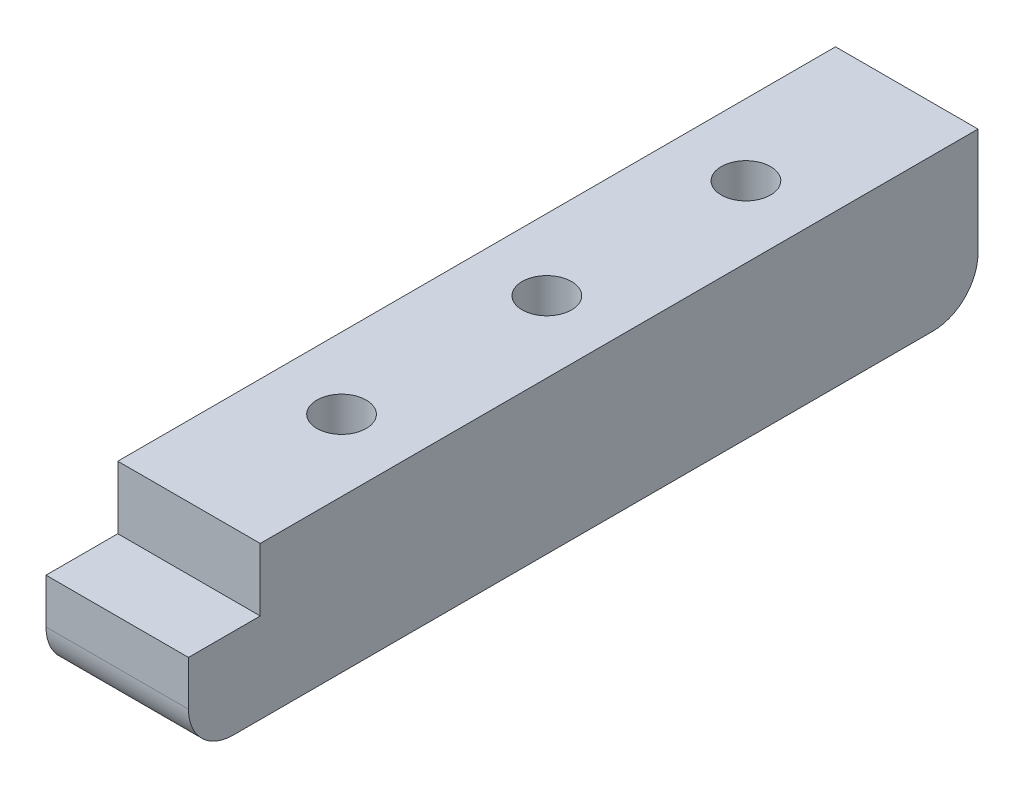
SolidWorks part; units mm, degrees
material "6063-T6"
ref_plane "Plano frontal" through (0, 0, 0) normal (0, 0, 1) x (1, 0, 0)
ref_plane "Plano superior" through (0, 0, 0) normal (0, 1, 0) x (1, 0, 0)
ref_plane "Plano direito" through (0, 0, 0) normal (1, 0, 0) x (0, 0, -1)
sketch "Esboço1" plane through (0, 0, 0) normal (1, 0, 0) x (0, 0, -1)
  line L1 (-17, -8.5) -> (63, -8.5)
  line L2 (-17, 1.5) -> (-17, 8.5)
  line L3 (-17, 8.5) -> (63, 8.5)
  line L4 (63, -8.5) -> (63, 8.5)
  line L7 (-17, -8.5) -> (-25, -8.5)
  line L9 (-17, 1.5) -> (-25, 1.5)
  line L10 (-25, -8.5) -> (-25, 1.5)
  point P0 (0, 0)
  dimension "D1" = 80
  dimension "D2" = 17
  dimension "D3" = 8
  dimension "D4" = 10
  dimension "D5" = 7
extrude "Ressalto-extrusão1" add sketch "Esboço1" along normal mid plane 15.88
fillet "Filete1" radius 5 2 edges at (0, -8.5, -63) (0, -8.5, 25)
hole_wizard "Escareado para SFHCS M51" positions "Esboço2" profile "Esboço3" countersink size "M5" standard "Ansi Metric"
sketch "Esboço2" plane through (-33.065, -8.5, -26.4602) normal (0, -1, 0) x (-1, 0, 0)
  line L5 (-33.065, -6.2661) -> (-33.065, -26.4602) construction
  line L6 (-33.065, -26.4602) -> (-33.065, -46.4602) construction
  line L8 (33.065, -46.4602) -> (33.065, -26.4602) construction
  line L10 (33.065, -26.4602) -> (33.065, -14.4602) construction
  point P12 (-33.065, 18.6124)
  point P22 (-33.065, -26.4602)
  point P38 (33.065, -26.4602)
  point P41 (33.065, -14.4602)
  point P44 (-33.065, -6.2661)
sketch "Esboço3" plane through (0, -8.5, -45.0726) normal (1, 0, 0) x (0, 0, -1)
  line L0 (0, 0) -> (0, 31.6524)
  line L1 (0, 31.6524) -> (2.75, 30)
  line L2 (2.75, 30) -> (2.75, 3.35)
  line L3 (2.75, 3.35) -> (5.6, 0.5)
  line L4 (5.6, 0.5) -> (5.6, 0)
  line L5 (5.6, 0) -> (0, 0)
  line L6 (-2.75, 3.35) -> (-5.6, 0.5) construction
  line L7 (0, 31.6524) -> (-2.75, 30) construction
  line L8 (0, -6.35) -> (0, 107.95) construction
  dimension "Hole Dia." = 5.5
  dimension "Hole Depth" = 30
  dimension "C'Sink Dia." = 11.2
  dimension "C'Sink Angle" = 90
  dimension "Drill Angle" = 118
  dimension "Head Clearance" = 0.5
sketch "Esboço4" plane through (0, -8.5, 0) normal (0, -1, 0) x (1, 0, 0)
  circle A0 centre (0, -22.8871) radius 5.5272
hole_wizard "Escareado para SFHCS M52" positions "Esboço5" profile "Esboço6" countersink size "M5" standard "Ansi Metric" end condition through all
sketch "Esboço5" plane through (0, -8.5, 0) normal (0, -1, 0) x (-1, 0, 0)
  point P0 (0, 22.8871)
sketch "Esboço6" plane through (0, -8.5, -22.8871) normal (1, 0, 0) x (0, 0, -1)
  line L0 (0, 0) -> (0, 17)
  line L1 (0, 17) -> (2.75, 17)
  line L2 (2.75, 17) -> (2.75, 2.85)
  line L3 (2.75, 2.85) -> (5.6, 0)
  line L5 (5.6, 0) -> (0, 0)
  line L6 (-2.75, 2.85) -> (-5.6, 0) construction
  line L11 (0, -6.35) -> (0, 107.95) construction
  dimension "Thru Hole Dia." = 5.5
  dimension "Thru Hole Depth" = 17
  dimension "Near C'Sink Dia." = 11.2
  dimension "Near C'Sink Angle" = 90
